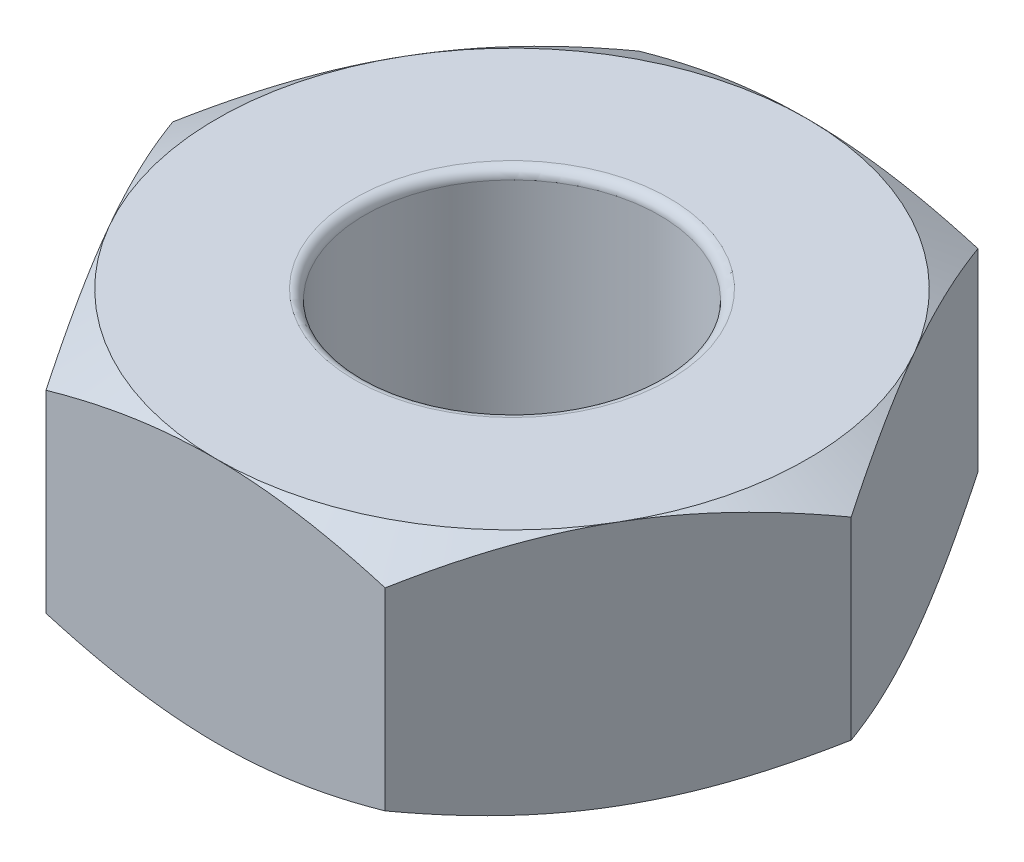
SolidWorks part; units mm, degrees
ref_plane "Front Plane" through (0, 0, 0) normal (0, 0, 1) x (1, 0, 0)
ref_plane "Top Plane" through (0, 0, 0) normal (0, 1, 0) x (1, 0, 0)
ref_plane "Right Plane" through (0, 0, 0) normal (1, 0, 0) x (0, 0, -1)
sketch "Sketch1" plane through (0, 0, 0) normal (0, 1, 0) x (1, 0, 0)
  line L1 (0.8729, 1.496) -> (-0.8592, 1.5039)
  line L2 (-0.8592, 1.5039) -> (-1.732, 0.0079)
  line L3 (-1.732, 0.0079) -> (-0.8729, -1.496)
  line L4 (-0.8729, -1.496) -> (0.8592, -1.5039)
  line L5 (0.8592, -1.5039) -> (1.732, -0.0079)
  line L6 (1.732, -0.0079) -> (0.8729, 1.496)
  circle A0 centre (0, 0) radius 0.75
  circle A1 centre (0, 0) radius 1.5 construction
  dimension "D1" = 1.5
  dimension "D2" = 3
extrude "Boss-Extrude1" add sketch "Sketch1" along normal blind 1.25
sketch "Sketch2" plane through (0, 1.25, 0) normal (0, 1, 0) x (1, 0, 0)
  circle A0 centre (0, 0) radius 1.5 construction
  circle A1 centre (0, 0) radius 1.5
extrude "Cut-Extrude2" cut sketch "Sketch2" against normal blind 1 draft 60 flip side to cut
sketch "Sketch3" plane through (0, 0, 0) normal (0, -1, 0) x (1, 0, 0)
  circle A0 centre (0, 0) radius 1.5 construction
  circle A1 centre (0, 0) radius 1.5
extrude "Cut-Extrude3" cut sketch "Sketch3" against normal blind 1 draft 60 flip side to cut
fillet "Fillet1" radius 0.05 2 edges at (0, 0, 0.75) (0, 1.25, 0.75)
